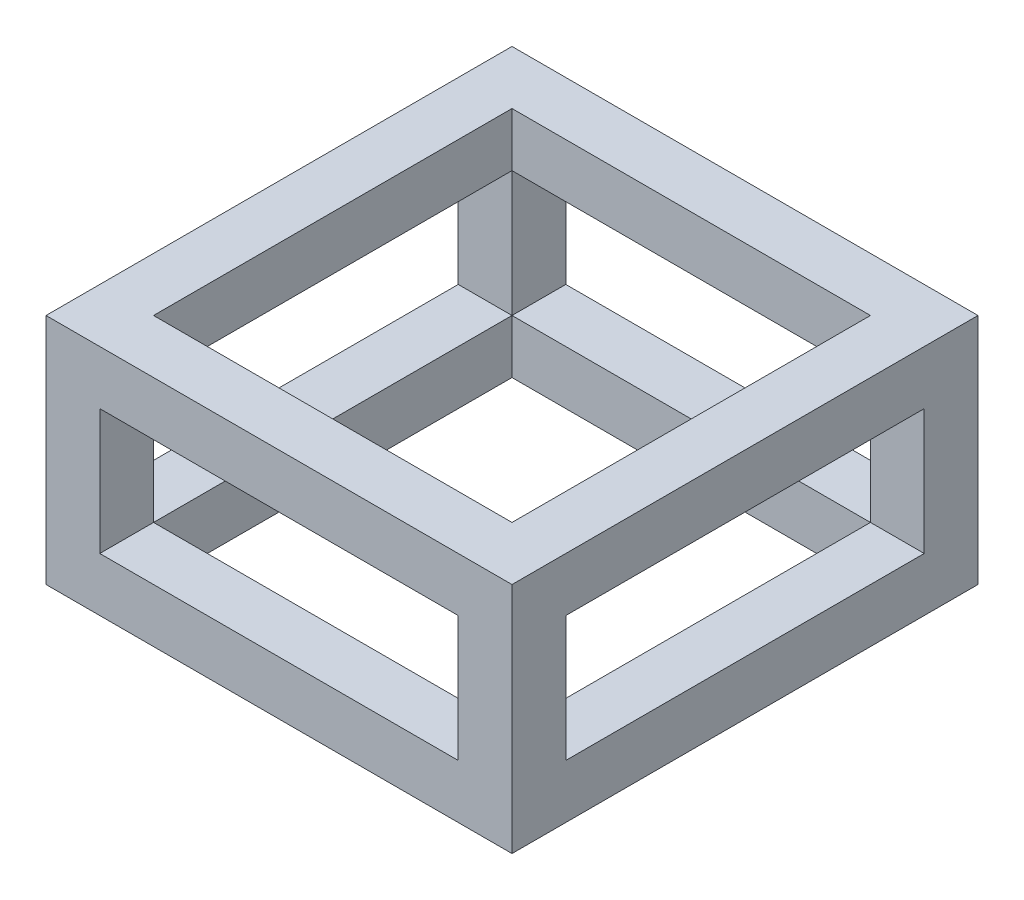
SolidWorks part; units mm, degrees
ref_plane "Front Plane" through (0, 0, 0) normal (0, 0, 1) x (1, 0, 0)
ref_plane "Top Plane" through (0, 0, 0) normal (0, 1, 0) x (1, 0, 0)
ref_plane "Right Plane" through (0, 0, 0) normal (1, 0, 0) x (0, 0, -1)
sketch "Sketch1" plane through (0, 0, 0) normal (0, 1, 0) x (1, 0, 0)
  line L1 (-65, 65) -> (65, 65)
  line L2 (-65, 65) -> (-65, -65)
  line L3 (-65, -65) -> (65, -65)
  line L4 (65, 65) -> (65, -65)
  line L5 (-65, 65) -> (65, -65) construction
  line L6 (-65, -65) -> (65, 65) construction
  line L7 (-50, 50) -> (50, 50)
  line L8 (-50, 50) -> (-50, -50)
  line L9 (-50, -50) -> (50, -50)
  line L10 (50, 50) -> (50, -50)
  line L11 (-50, 50) -> (50, -50) construction
  line L12 (-50, -50) -> (50, 50) construction
  point P0 (0, 0)
  point P6 (0, 0)
  dimension "D1" = 15
  dimension "D2" = 15
  dimension "D3" = 130
  dimension "D4" = 130
extrude "Boss-Extrude1" add sketch "Sketch1" along normal blind 15
sketch "Sketch2" plane through (0, 15, 0) normal (0, 1, 0) x (1, 0, 0)
  line L1 (-65, 65) -> (-50, 65)
  line L2 (-65, 65) -> (-65, 50)
  line L3 (-65, 50) -> (-50, 50)
  line L4 (-50, 65) -> (-50, 50)
  line L5 (50, 50) -> (65, 50)
  line L6 (50, 50) -> (50, 65)
  line L7 (50, 65) -> (65, 65)
  line L8 (65, 50) -> (65, 65)
  line L9 (65, -65) -> (50, -65)
  line L10 (65, -65) -> (65, -50)
  line L11 (65, -50) -> (50, -50)
  line L12 (50, -65) -> (50, -50)
  line L13 (-50, -50) -> (-65, -50)
  line L14 (-50, -50) -> (-50, -65)
  line L15 (-50, -65) -> (-65, -65)
  line L16 (-65, -50) -> (-65, -65)
extrude "Boss-Extrude2" add sketch "Sketch2" along normal blind 35
sketch "Sketch3" plane through (0, 50, 0) normal (0, 1, 0) x (1, 0, 0)
  line L1 (-65, 65) -> (65, 65)
  line L2 (-65, 65) -> (-65, -65)
  line L3 (-65, -65) -> (65, -65)
  line L4 (65, 65) -> (65, -65)
  line L5 (-50, 50) -> (50, 50)
  line L6 (-50, 50) -> (-50, -50)
  line L7 (-50, -50) -> (50, -50)
  line L8 (50, 50) -> (50, -50)
extrude "Boss-Extrude3" add sketch "Sketch3" along normal blind 15
